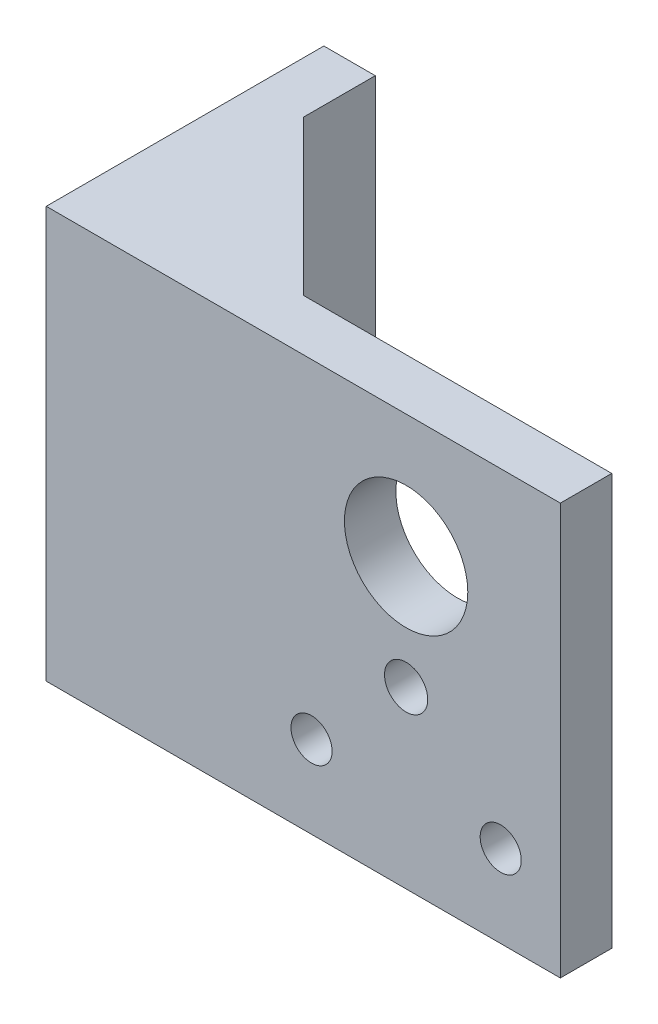
SolidWorks part; units mm, degrees
ref_plane "Front Plane" through (0, 0, 0) normal (0, 0, 1) x (1, 0, 0)
ref_plane "Top Plane" through (0, 0, 0) normal (0, 1, 0) x (1, 0, 0)
ref_plane "Right Plane" through (0, 0, 0) normal (1, 0, 0) x (0, 0, -1)
sketch "Sketch1" plane through (0, 0, 0) normal (0, 1, 0) x (1, 0, 0)
  line L7 (0, 0) -> (50, 0)
  line L8 (50, 0) -> (50, 5)
  line L9 (50, 5) -> (20, 5)
  line L10 (5, 20) -> (5, 35)
  line L11 (5, 35) -> (0, 35)
  line L12 (0, 35) -> (0, 0)
  line L13 (5, 20) -> (20, 5)
  dimension "D1" = 50
extrude "Boss-Extrude1" add sketch "Sketch1" along normal blind 40 contours L8 L9 L13 L10 L11 L12 L7
sketch "Sketch3" plane through (0, 0, 0) normal (0, -1, 0) x (1, 0, 0)
  line L0 (5, -20) -> (5, -5)
  line L1 (5, -5) -> (20, -5)
  line L2 (5, -20) -> (20, -5)
extrude "Cut-Extrude1" cut sketch "Sketch3" against normal blind 35 contours L2 L1 L0
sketch "Sketch5" plane through (0, 0, 0) normal (0, -1, 0) x (1, 0, 0)
  line L0 (5, -20) -> (5, -5)
  line L1 (5, -5) -> (5, -35) construction
  line L2 (5, -5) -> (20, -5)
  line L3 (50, -5) -> (5, -5) construction
  line L4 (20, -5) -> (5, -20)
extrude "Boss-Extrude2" add sketch "Sketch5" against normal blind 5 contours L4 L0 L2
sketch "Sketch6" plane through (5, 0, 0) normal (1, 0, 0) x (0, 0, -1)
  line L0 (13, 30) -> (13, 10) construction
  line L2 (13, 20) -> (21, 20) construction
  line L3 (5, 35) -> (5, 5) construction
  circle A2 centre (13, 30) radius 2
  circle A4 centre (13, 10) radius 2
  circle A5 centre (21, 20) radius 2
  dimension "D1" = 4
  dimension "D2" = 8
  dimension "D3" = 8
  dimension "D4" = 8
  dimension "D7" = 20
extrude "Cut-Extrude2" cut sketch "Sketch6" against normal through all
sketch "Sketch7" plane through (0, 0, -5) normal (0, 0, -1) x (-1, 0, 0)
  line L7 (-50, 40) -> (-50, 0) construction
  line L8 (-50, 40) -> (-20, 40) construction
  circle A0 centre (-35, 28) radius 3.2
  circle A1 centre (-35, 17) radius 2.1
  circle A2 centre (-25.8, 8) radius 2
  circle A3 centre (-44.2, 8) radius 2
  dimension "D1" = 5.8
  dimension "D2" = 18.4
  dimension "D3" = 11
  dimension "D4" = 12
  dimension "D5" = 15
  dimension "D6" = 15
extrude "Cut-Extrude4" cut sketch "Sketch7" against normal blind 18.4
sketch "Sketch9" plane through (0, 0, 0) normal (0, 0, 1) x (1, 0, 0)
  circle A0 centre (35, 28) radius 5.05
extrude "Cut-Extrude5" cut sketch "Sketch9" against normal blind 3
sketch "Sketch10" plane through (0, 0, 0) normal (0, 0, 1) x (1, 0, 0)
  circle A0 centre (35, 28) radius 6
extrude "Cut-Extrude6" cut sketch "Sketch10" against normal through all
sketch "Sketch11" plane through (5, 0, 0) normal (1, 0, 0) x (0, 0, -1)
  line L0 (20, 0) -> (35, 0) construction
  line L1 (35, 40) -> (27, 40)
  line L2 (35, 40) -> (35, 0)
  line L3 (35, 0) -> (27, 0)
  line L4 (27, 40) -> (27, 0)
  dimension "D1" = 8
extrude "Cut-Extrude7" cut sketch "Sketch11" against normal through all
